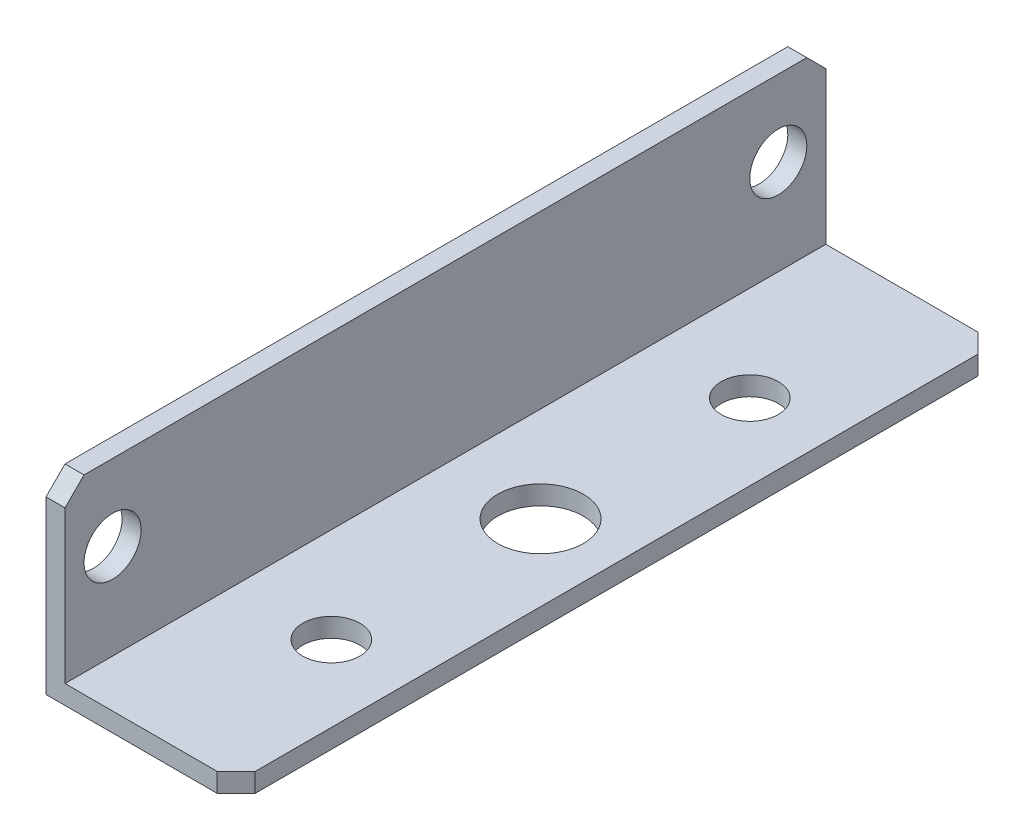
SolidWorks part; units mm, degrees
ref_plane "Ebene vorne" through (0, 0, 0) normal (0, 0, 1) x (1, 0, 0)
ref_plane "Ebene oben" through (0, 0, 0) normal (0, 1, 0) x (1, 0, 0)
ref_plane "Ebene rechts" through (0, 0, 0) normal (1, 0, 0) x (0, 0, -1)
sketch "Skizze1" plane through (0, 0, 0) normal (0, 0, 1) x (1, 0, 0)
  line L0 (0, 10) -> (0, 0)
  line L1 (0, 0) -> (10, 0)
  dimension "D1" = 10
extrude "Linear-Austragen-Dünn1" add sketch "Skizze1" along normal mid plane 40 thin thin type one direction reverse wall 1
chamfer "Fase1" distance 1 angle 45 4 edges at (0.5, 10, -20) (10, 0.5, -20) (10, 0.5, 20) (0.5, 10, 20)
sketch "Skizze2" plane through (1, 0, 0) normal (1, 0, 0) x (0, 0, -1)
  line L0 (-17.5, 6) -> (17.5, 6) construction
  line L1 (-19, 10) -> (19, 10) construction
  circle A0 centre (-17.5, 6) radius 1.5
  circle A1 centre (17.5, 6) radius 1.5
  point P2 (0, 6)
  dimension "D3" = 3
  dimension "D1" = 35
  dimension "D2" = 4
extrude "Schnitt-Linear austragen1" cut sketch "Skizze2" against normal blind 10
sketch "Skizze3" plane through (0, 1, 0) normal (0, 1, 0) x (1, 0, 0)
  line L0 (6, -11) -> (6, 11) construction
  line L1 (10, -19) -> (10, 19) construction
  circle A0 centre (6, -11) radius 1.5
  circle A1 centre (6, 11) radius 1.5
  point P2 (6, 0)
  dimension "D3" = 3
  dimension "D1" = 22
  dimension "D2" = 4
extrude "Schnitt-Linear austragen2" cut sketch "Skizze3" against normal blind 10
sketch "Skizze4" plane through (0, 1, 0) normal (0, 1, 0) x (1, 0, 0)
  line L0 (6, -11) -> (6, 11) construction
  circle A0 centre (6, 0) radius 2.25
  dimension "D1" = 4.5
extrude "Schnitt-Linear austragen3" cut sketch "Skizze4" against normal blind 10
